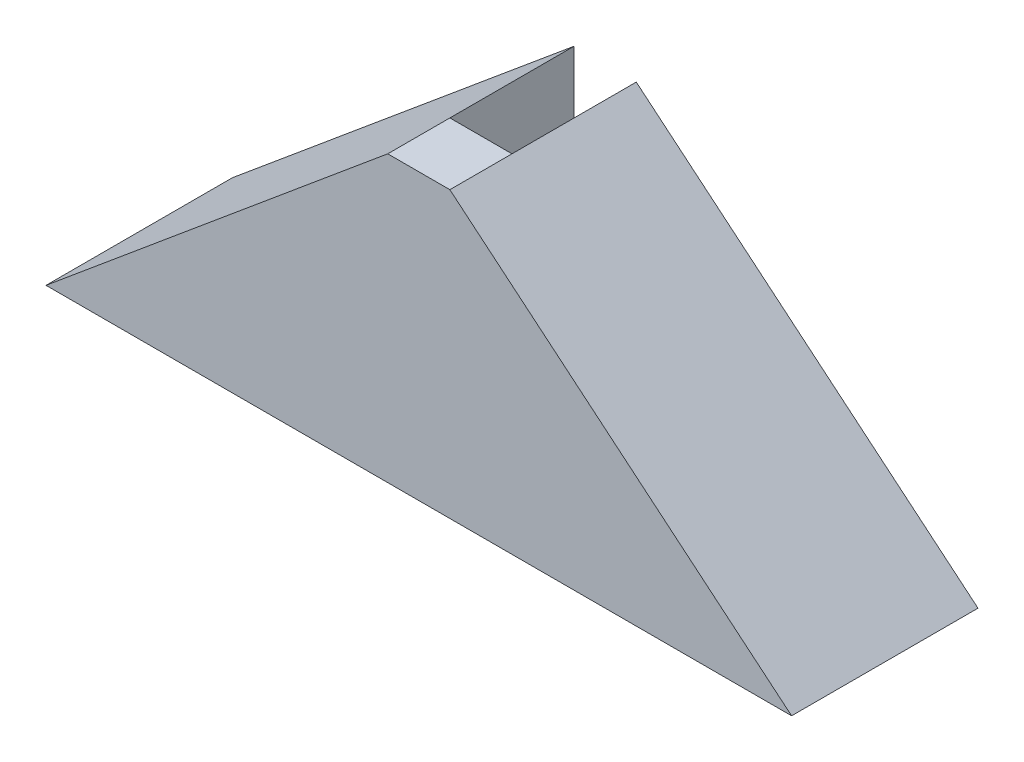
SolidWorks part; units mm, degrees
ref_plane "Front" through (0, 0, 0) normal (0, 0, 1) x (1, 0, 0)
ref_plane "Top" through (0, 0, 0) normal (0, 1, 0) x (1, 0, 0)
ref_plane "Right" through (0, 0, 0) normal (1, 0, 0) x (0, 0, -1)
sketch "Sketch2" plane through (0, 0, 0) normal (0, 0, 1) x (1, 0, 0)
  line L9 (0, 0) -> (-30.48, 0)
  line L10 (0, 0) -> (-15.24, 12.7)
  line L11 (-15.24, 12.7) -> (-30.48, 0)
  point P2 (0, 0)
  point P4 (-15.24, 0)
  dimension "D1" = 30.48
  dimension "D2" = 12.7
extrude "Boss-Extrude1" add sketch "Sketch2" along normal blind 7.62
sketch "Sketch5" plane through (0, 0, 0) normal (0, 0, -1) x (-1, 0, 0)
  line L0 (15.24, 12.7) -> (15.24, 0) construction
  line L1 (16.51, 0) -> (13.97, 0)
  line L2 (16.51, 0) -> (16.51, 12.7)
  line L3 (16.51, 12.7) -> (13.97, 12.7)
  line L4 (13.97, 0) -> (13.97, 12.7)
  line L5 (0, 0) -> (30.48, 0) construction
  point P9 (15.24, 12.7)
  point P10 (0, 0)
  dimension "D1" = 2.54
extrude "Cut-Extrude2" cut sketch "Sketch5" against normal blind 5.08
sketch "Sketch6" plane through (0, 0, 5.08) normal (0, 0, -1) x (-1, 0, 0)
  line L1 (13.97, 11.6417) -> (16.51, 11.6417)
  line L2 (13.97, 11.6417) -> (13.97, 12.7)
  line L3 (13.97, 12.7) -> (16.51, 12.7)
  line L4 (16.51, 11.6417) -> (16.51, 12.7)
extrude "Cut-Extrude3" cut sketch "Sketch6" against normal through all and the other way through all
